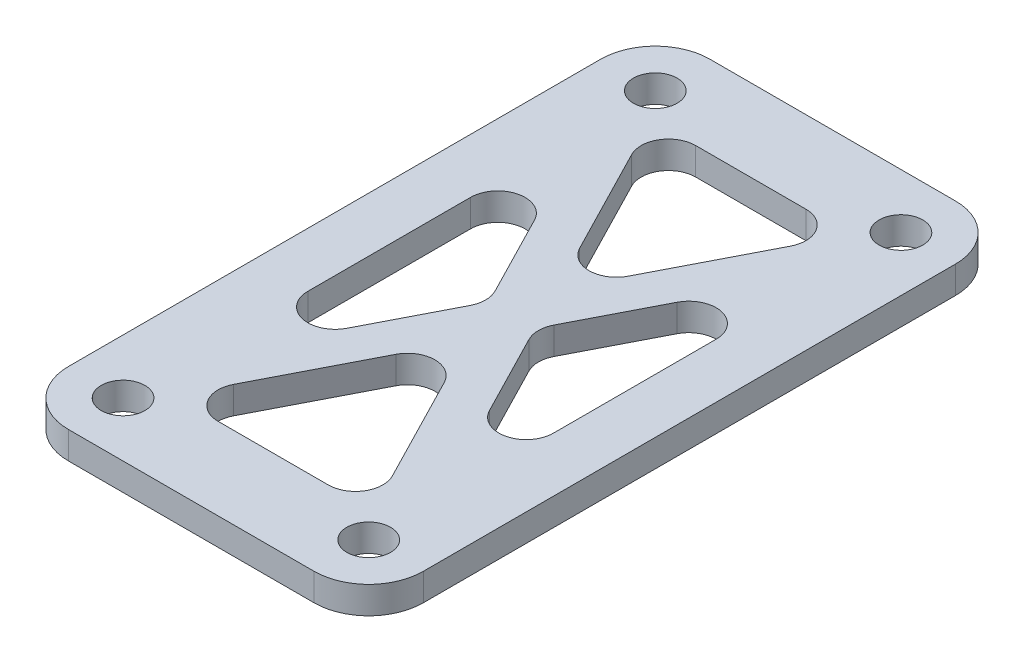
SolidWorks part; units mm, degrees
material "ABS"
ref_plane "Front Plane" through (0, 0, 0) normal (0, 0, 1) x (1, 0, 0)
ref_plane "Top Plane" through (0, 0, 0) normal (0, 1, 0) x (1, 0, 0)
ref_plane "Right Plane" through (0, 0, 0) normal (1, 0, 0) x (0, 0, -1)
other "Configuration Table"
sketch "Sketch1" plane through (0, 0, 0) normal (0, 1, 0) x (1, 0, 0)
  line L6 (-4, 4) -> (22, 4)
  line L7 (-4, 4) -> (-4, -43)
  line L8 (-4, -43) -> (22, -43)
  line L9 (22, 4) -> (22, -43)
  circle B0 centre (0, -39) radius 1.6
  circle B1 centre (18, 0) radius 1.6
  circle B2 centre (0, 0) radius 1.6
  circle B3 centre (18, -39) radius 1.6
  dimension "D1" = 4
  dimension "D2" = 4
  dimension "D3" = 4
  dimension "D4" = 4
  dimension "D5" = 4
sketch_block_instance "Block2-1"
sketch_block "Block2"
extrude "Boss-Extrude1" add sketch "Sketch1" along normal blind 2
fillet "Fillet1" radius 4 4 edges at (-4, 1, -4) (22, 1, -4) (22, 1, 43) (-4, 1, 43)
sketch "Sketch2" plane through (0, 2, 0) normal (0, 1, 0) x (1, 0, 0)
  line L0 (0, 0) -> (18, -39) construction
  line L5 (-4, 0) -> (-4, -39) construction
  line L6 (18, -2) -> (0, -2)
  line L7 (18, -2) -> (18, -37)
  line L8 (18, -37) -> (0, -37)
  line L9 (0, -2) -> (0, -37)
  line L10 (18, -2) -> (0, -37) construction
  line L11 (18, -37) -> (0, -2) construction
  line L12 (18, 4) -> (0, 4) construction
  point P2 (9, -19.5)
  point P9 (1.2299, -35.0055)
  dimension "D1" = 4
  dimension "D2" = 6
extrude "Cut-Extrude1" cut sketch "Sketch2" against normal blind 2
sketch "Sketch3" plane through (0, 2, 0) normal (0, 1, 0) x (1, 0, 0)
  line L0 (0, -2) -> (18, -37)
  line L1 (18, -2) -> (0, -37)
  line L2 (0, -37) -> (18, -37) construction
  line L3 (0, -2) -> (0, -37) construction
extrude "Extrude-Thin1" add sketch "Sketch3" against normal blind 2 thin thin type mid plane wall 3
fillet "Fillet2" radius 2 12 edges at (18, 1, 33.7202) (10.6867, 1, 19.5) (18, 1, 5.2798) (1.6867, 1, 37) (9, 1, 22.7798) (16.3133, 1, 37) (16.3133, 1, 2) (9, 1, 16.2202) (7.3133, 1, 19.5) (0, 1, 33.7202) (0, 1, 5.2798) (1.6867, 1, 2)
